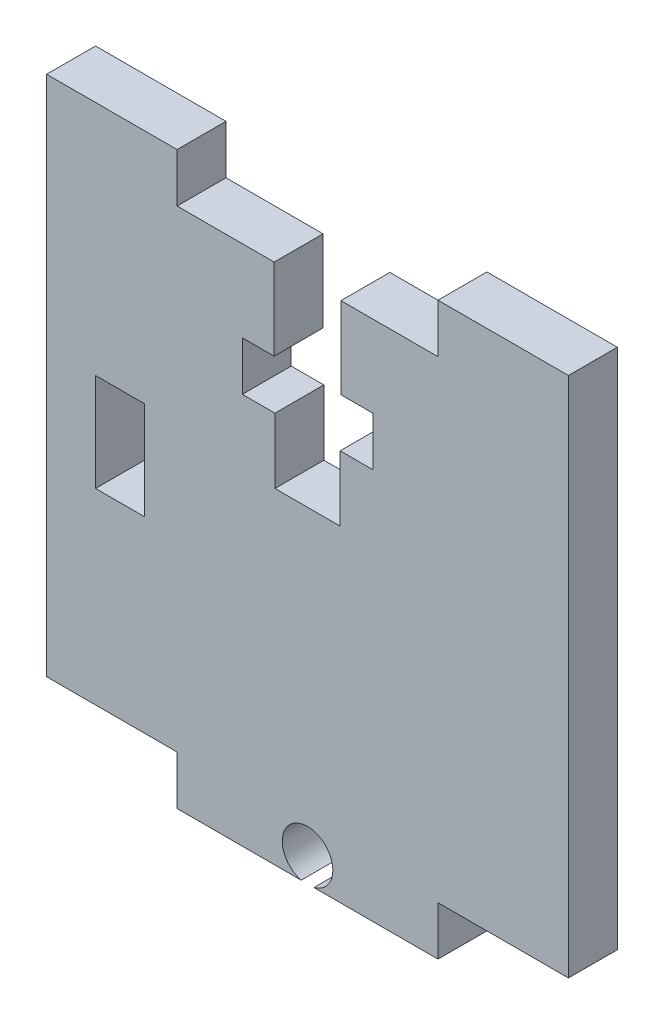
SolidWorks part; units mm, degrees
ref_plane "前视" through (0, 0, 0) normal (0, 0, 1) x (1, 0, 0)
ref_plane "上视" through (0, 0, 0) normal (0, 1, 0) x (1, 0, 0)
ref_plane "右视" through (0, 0, 0) normal (1, 0, 0) x (0, 0, -1)
sketch "草图2" plane through (0, 0, 0) normal (0, 0, 1) x (1, 0, 0)
  line L0 (0, 103.0974) -> (0, -63.3868) construction
  line L1 (2.0479, 48.8553) -> (8, 48.8553)
  line L2 (8, 48.8553) -> (8, 51.8553)
  line L3 (8, 51.8553) -> (16, 51.8553)
  line L4 (16, 51.8553) -> (16, 19.8553)
  line L5 (16, 19.8553) -> (8, 19.8553)
  line L6 (2.0479, 48.8553) -> (2.0479, 43.8553)
  line L7 (2.0479, 43.8553) -> (4, 43.8553)
  line L8 (4, 43.8553) -> (4, 40.8553)
  line L9 (4, 40.8553) -> (2, 40.8553)
  line L10 (2, 40.8553) -> (2, 36.8553)
  line L11 (2, 36.8553) -> (-2, 36.8553)
  line L12 (-8, 16.8553) -> (-0.3905, 16.8553)
  line L13 (8, 16.8553) -> (8, 19.8553)
  line L14 (-8, 16.8553) -> (-8, 19.8553)
  line L15 (0.3905, 16.8553) -> (8, 16.8553)
  line L16 (-2, 40.8553) -> (-2, 36.8553)
  line L17 (-4, 40.8553) -> (-2, 40.8553)
  line L18 (-4, 43.8553) -> (-4, 40.8553)
  line L19 (-2.0479, 43.8553) -> (-4, 43.8553)
  line L20 (-2.0479, 48.8553) -> (-2.0479, 43.8553)
  line L21 (-16, 19.8553) -> (-8, 19.8553)
  line L22 (-16, 51.8553) -> (-16, 19.8553)
  line L23 (-8, 51.8553) -> (-16, 51.8553)
  line L24 (-8, 48.8553) -> (-8, 51.8553)
  line L25 (-2.0479, 48.8553) -> (-8, 48.8553)
  line L27 (-13, 31.3553) -> (-10, 31.3553)
  line L28 (-13, 31.3553) -> (-13, 37.3553)
  line L29 (-13, 37.3553) -> (-10, 37.3553)
  line L30 (-10, 31.3553) -> (-10, 37.3553)
  arc A0 (0.3905, 16.8553) -> (-0.3905, 16.8553) centre (0, 18.3553) ccw
  point P22 (0, 36.8553)
  dimension "D12" = 1.5
  dimension "D11" = 3.1
  dimension "D1" = 8
  dimension "D2" = 8
  dimension "D3" = 3
  dimension "D4" = 12
  dimension "D5" = 5
  dimension "D6" = 3
  dimension "D7" = 2
  dimension "D8" = 2
  dimension "D9" = 32
  dimension "D10" = 3
  dimension "D13" = 3
  dimension "D14" = 6
  dimension "D15" = 3
  dimension "D16" = 11.5
extrude "凸台-拉伸1" add sketch "草图2" along normal blind 3
